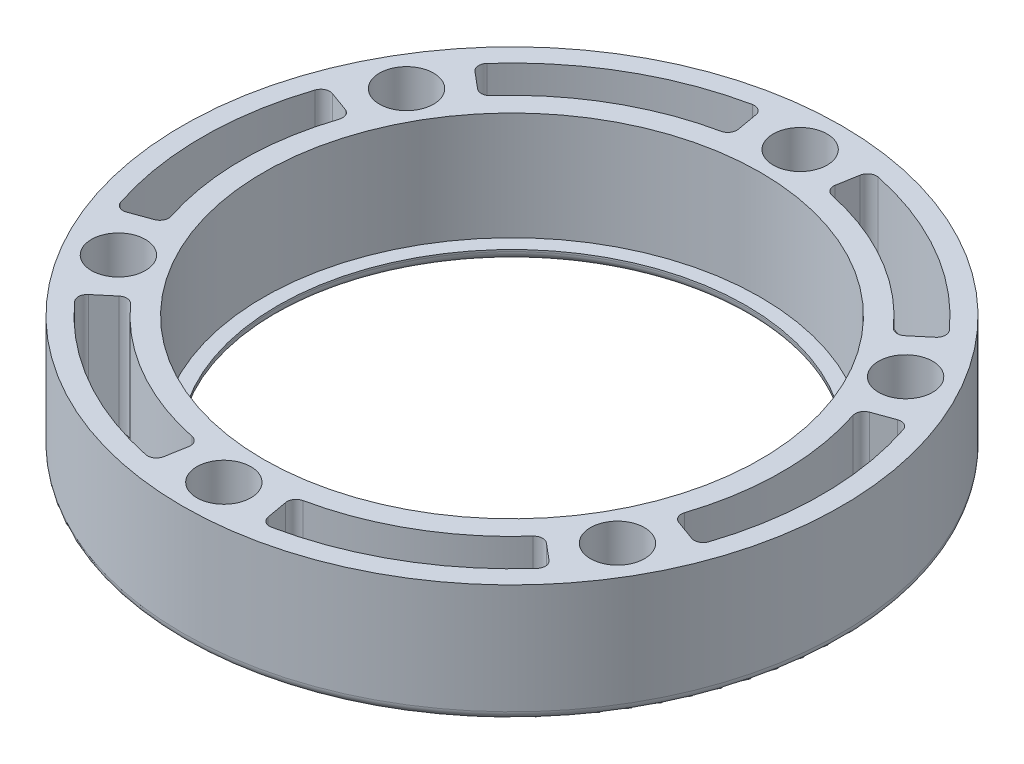
SolidWorks part; units mm, degrees
material "2024-T4"
ref_plane "前视基准面" through (0, 0, 0) normal (0, 0, 1) x (1, 0, 0)
ref_plane "上视基准面" through (0, 0, 0) normal (0, 1, 0) x (1, 0, 0)
ref_plane "右视基准面" through (0, 0, 0) normal (1, 0, 0) x (0, 0, -1)
sketch "草图1" plane through (0, 0, 0) normal (1, 0, 0) x (0, 0, -1)
  line L0 (0, 0) -> (0, 159.2157) construction
  line L1 (-91.5, 33) -> (-91.5, 0)
  line L2 (-91.5, 0) -> (-65, 0)
  line L3 (-65, 0) -> (-65, 3)
  line L4 (-65, 3) -> (-69, 3)
  line L5 (-69, 3) -> (-69, 33)
  line L6 (-69, 33) -> (-91.5, 33)
  dimension "D1" = 130
  dimension "D2" = 138
  dimension "D3" = 33
  dimension "D4" = 3
  dimension "D5" = 183
revolve "旋转1" add sketch "草图1" angle 360 about L0
sketch "草图2" plane through (0, 33, 0) normal (0, 1, 0) x (1, 0, 0)
  circle A0 centre (0, 80) radius 7.5
  point P2 (-3.6115, 79.9184)
  point P3 (0, 0)
  point P6 (-2.8074, 60.0539)
  dimension "D2" = 15
  dimension "D4" = 80
extrude "切除-拉伸1" cut sketch "草图2" against normal through all
sketch "草图3" plane through (0, 33, 0) normal (0, 1, 0) x (1, 0, 0)
  line L0 (-31.5636, 0) -> (0, 0) construction
  line L1 (0, 0) -> (-70.4769, 25.6515) construction
  line L2 (-72.7883, 26.4928) -> (-78.4292, 28.5459)
  line L3 (-80.8136, 29.4137) -> (-80.8136, -29.4137) construction
  line L4 (-78.4292, -28.5459) -> (-72.7883, -26.4928)
  line L5 (-70.4769, -25.6515) -> (0, 0) construction
  arc A0 (-71.2677, 23.3647) -> (-71.2677, -23.3647) centre (0, 0) ccw
  arc A1 (-81.658, 26.981) -> (-81.658, -26.981) centre (0, 0) ccw
  arc A2 (-81.658, -26.981) -> (-78.4292, -28.5459) centre (-79.2842, -26.1966) ccw
  arc A3 (-71.2677, -23.3647) -> (-72.7883, -26.4928) centre (-73.6433, -24.1435) cw
  arc A4 (-71.2677, 23.3647) -> (-72.7883, 26.4928) centre (-73.6433, 24.1435) ccw
  arc A5 (-81.658, 26.981) -> (-78.4292, 28.5459) centre (-79.2842, 26.1966) cw
  dimension "D2" = 75
  dimension "D3" = 86
  dimension "D4" = 2.5
  dimension "D1" = 40
extrude "切除-拉伸2" cut sketch "草图3" against normal through all
pattern_circular "阵列(圆周)1" count 6 over 360 about axis through (0, 0, 0) along (0, 1, 0) of "切除-拉伸1", "切除-拉伸2"
fillet "圆角1" radius 2.5 2 edges at (0, 0, -65) (0, 0, -91.5)
